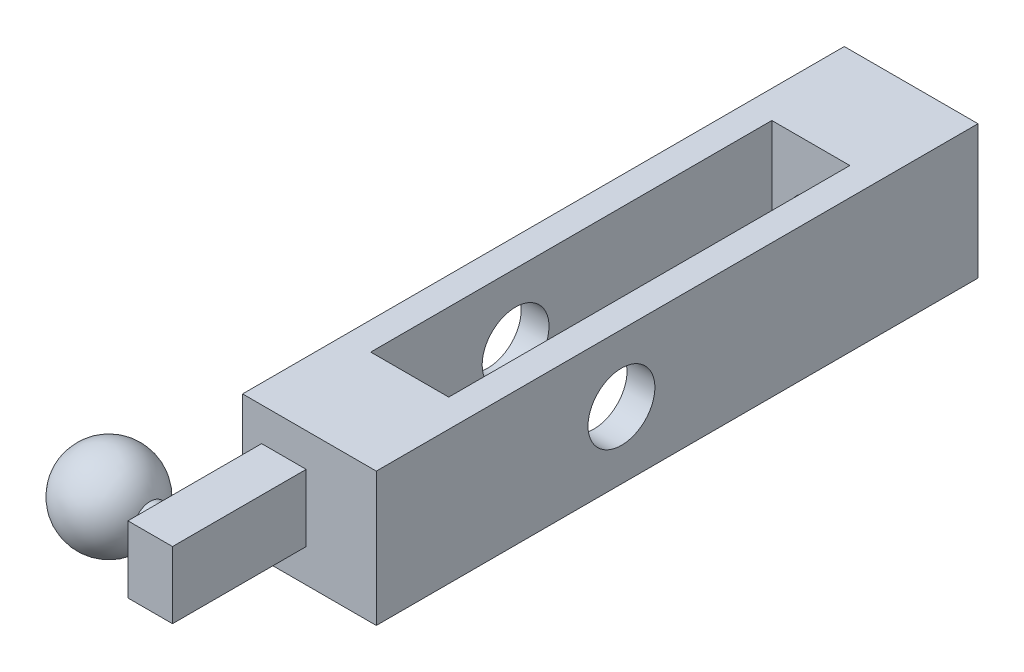
SolidWorks part; units mm, degrees
ref_plane "前视基准面" through (0, 0, 0) normal (0, 0, 1) x (1, 0, 0)
ref_plane "上视基准面" through (0, 0, 0) normal (0, 1, 0) x (1, 0, 0)
ref_plane "右视基准面" through (0, 0, 0) normal (1, 0, 0) x (0, 0, -1)
other "Configuration Table"
sketch "草图1" plane through (0, 0, 0) normal (0, 0, 1) x (1, 0, 0)
  line L1 (3, -3) -> (-3, -3)
  line L2 (3, -3) -> (3, 3)
  line L3 (3, 3) -> (-3, 3)
  line L4 (-3, -3) -> (-3, 3)
  line L5 (3, -3) -> (-3, 3) construction
  line L6 (3, 3) -> (-3, -3) construction
  point P0 (0, 0)
  dimension "D1" = 6
  dimension "D2" = 6
extrude "凸台-拉伸1" add sketch "草图1" along normal blind 27
sketch "草图2" plane through (0, 0, 27) normal (0, 0, 1) x (1, 0, 0)
  line L1 (-2.1448, 1.4955) -> (-0.1448, 1.4955)
  line L2 (-2.1448, 1.4955) -> (-2.1448, -1.5045)
  line L3 (-2.1448, -1.5045) -> (-0.1448, -1.5045)
  line L4 (-0.1448, 1.4955) -> (-0.1448, -1.5045)
  line L5 (-2.1448, 1.4955) -> (-0.1448, -1.5045) construction
  line L6 (-2.1448, -1.5045) -> (-0.1448, 1.4955) construction
  point P0 (-1.1448, -0.0045)
  dimension "D1" = 2
  dimension "D2" = 3
extrude "凸台-拉伸2" add sketch "草图2" along normal blind 6
sketch "草图3" plane through (-2.1448, 0, 0) normal (-1, 0, 0) x (0, 0, 1)
  circle A0 centre (31, 0) radius 0.75
  dimension "D1" = 1.5
  dimension "D2" = 31
extrude "凸台-拉伸3" add sketch "草图3" along normal blind 1
sketch "草图4" plane through (0, 0, 0) normal (0, 1, 0) x (1, 0, 0)
  line L0 (-3.1448, -31) -> (-6.9988, -31)
  line L1 (-3.1448, -30.25) -> (-3.1448, -31.75) construction
  line L2 (-3.1448, -31) -> (-3.1448, -30.25)
  arc A0 (-3.1448, -30.25) -> (-6.9988, -31) centre (-4.9988, -31) ccw
  dimension "D1" = 4
revolve "旋转1" add sketch "草图4" angle 360 about L0
sketch "草图5" plane through (0.5, 3, 0) normal (0, -1, 0) x (0, 0, 1)
  line L0 (27, 3.5) -> (0, 3.5) construction
  line L1 (4.5, 2.25) -> (22.5, 2.25)
  line L2 (4.5, 2.25) -> (4.5, -1.25)
  line L3 (4.5, -1.25) -> (22.5, -1.25)
  line L4 (22.5, 2.25) -> (22.5, -1.25)
  point P4 (4.5, 0.5)
  point P8 (13.5, 3.5)
  point P9 (13.5, 2.25)
  dimension "D1" = 18
  dimension "D2" = 3.5
extrude "切除-拉伸1" cut sketch "草图5" along normal blind 8
sketch "草图6" plane through (-3, 0, 0) normal (-1, 0, 0) x (0, 0, 1)
  line L0 (0, 3) -> (0, -3) construction
  circle A0 centre (16, 0) radius 1.5
  dimension "D1" = 3
  dimension "D2" = 16
extrude "切除-拉伸2" cut sketch "草图6" against normal blind 8
sketch "草图7" plane through (0, 0, 0) normal (0, 0, -1) x (-1, 0, 0)
  circle A0 centre (0, 0) radius 0.9
  dimension "D1" = 1.8
extrude "切除-拉伸3" cut sketch "草图7" against normal blind 8
